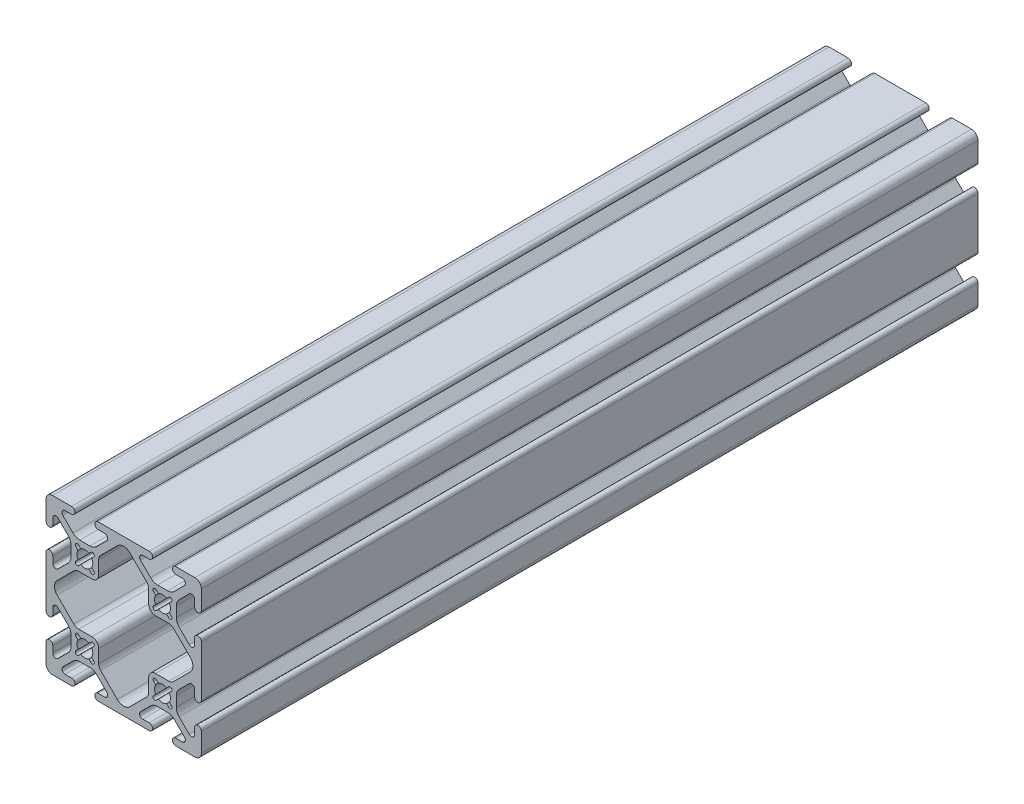
SolidWorks part; units mm, degrees
material "6105-T5 Aluminum"
ref_plane "Front Plane" through (0, 0, 0) normal (0, 0, 1) x (1, 0, 0)
ref_plane "Top Plane" through (0, 0, 0) normal (0, 1, 0) x (1, 0, 0)
ref_plane "Right Plane" through (0, 0, 0) normal (1, 0, 0) x (0, 0, -1)
sketch "Sketch1" plane through (0, 0, 0) normal (0, 0, 1) x (1, 0, 0)
  line L0 (-14.6692, 15.5605) -> (-14.0405, 14.9319)
  line L1 (-11.3595, 14.9319) -> (-10.7308, 15.5605)
  line L2 (-9.8395, 14.6692) -> (-10.4681, 14.0405)
  line L3 (-10.4681, 11.3595) -> (-9.8395, 10.7308)
  line L4 (-10.7308, 9.8395) -> (-11.3595, 10.4681)
  line L5 (-14.0405, 10.4681) -> (-14.6692, 9.8395)
  line L6 (-15.5605, 10.7308) -> (-14.9319, 11.3595)
  line L7 (-14.9319, 14.0405) -> (-15.5605, 14.6692)
  line L8 (11.3595, 10.4681) -> (10.7308, 9.8395)
  line L9 (9.8395, 10.7308) -> (10.4681, 11.3595)
  line L10 (10.4681, 14.0405) -> (9.8395, 14.6692)
  line L11 (10.7308, 15.5605) -> (11.3595, 14.9319)
  line L12 (14.0405, 14.9319) -> (14.6692, 15.5605)
  line L13 (15.5605, 14.6692) -> (14.9319, 14.0405)
  line L14 (14.9319, 11.3595) -> (15.5605, 10.7308)
  line L15 (14.6692, 9.8395) -> (14.0405, 10.4681)
  line L16 (-14.6692, -9.8395) -> (-14.0405, -10.4681)
  line L17 (-11.3595, -10.4681) -> (-10.7308, -9.8395)
  line L18 (-9.8395, -10.7308) -> (-10.4681, -11.3595)
  line L19 (-10.4681, -14.0405) -> (-9.8395, -14.6692)
  line L20 (-10.7308, -15.5605) -> (-11.3595, -14.9319)
  line L21 (-14.0405, -14.9319) -> (-14.6692, -15.5605)
  line L22 (-15.5605, -14.6692) -> (-14.9319, -14.0405)
  line L23 (-14.9319, -11.3595) -> (-15.5605, -10.7308)
  line L24 (10.7308, -9.8395) -> (11.3595, -10.4681)
  line L25 (14.0405, -10.4681) -> (14.6692, -9.8395)
  line L26 (15.5605, -10.7308) -> (14.9319, -11.3595)
  line L27 (14.9319, -14.0405) -> (15.5605, -14.6692)
  line L28 (14.6692, -15.5605) -> (14.0405, -14.9319)
  line L29 (11.3595, -14.9319) -> (10.7308, -15.5605)
  line L30 (9.8395, -14.6692) -> (10.4681, -14.0405)
  line L31 (10.4681, -11.3595) -> (9.8395, -10.7308)
  line L32 (7.5356, -16.3017) -> (2.0587, -21.7787)
  line L33 (-2.0587, -21.7787) -> (-7.5356, -16.3017)
  line L34 (-8.1828, -14.7392) -> (-8.1828, -10.3926)
  line L35 (-10.3926, -8.1828) -> (-14.7392, -8.1828)
  line L36 (-16.3017, -7.5356) -> (-21.7787, -2.0587)
  line L37 (-21.7787, 2.0587) -> (-16.3017, 7.5356)
  line L38 (-14.7392, 8.1828) -> (-10.3926, 8.1828)
  line L39 (-8.1828, 10.3926) -> (-8.1828, 14.7392)
  line L40 (-7.5356, 16.3017) -> (-2.0587, 21.7787)
  line L41 (2.0587, 21.7787) -> (7.5356, 16.3017)
  line L42 (8.1828, 14.7392) -> (8.1828, 10.3926)
  line L43 (10.3926, 8.1828) -> (14.7392, 8.1828)
  line L44 (16.3017, 7.5356) -> (21.7787, 2.0587)
  line L45 (21.7787, -2.0587) -> (16.3017, -7.5356)
  line L46 (14.7392, -8.1828) -> (10.3926, -8.1828)
  line L47 (8.1828, -10.3926) -> (8.1828, -14.7392)
  line L48 (25.4, 17.0561) -> (25.4, 23.2918)
  line L49 (23.2918, 25.4) -> (17.0561, 25.4)
  line L50 (17.0561, 23.1902) -> (19.1749, 23.1902)
  line L51 (19.8933, 21.4558) -> (16.5846, 18.1471)
  line L52 (14.3396, 17.2172) -> (11.0604, 17.2172)
  line L53 (8.8154, 18.1471) -> (5.5067, 21.4558)
  line L54 (6.2251, 23.1902) -> (8.3439, 23.1902)
  line L55 (8.3439, 25.4) -> (-8.3439, 25.4)
  line L56 (-8.3439, 23.1902) -> (-6.2251, 23.1902)
  line L57 (-5.5067, 21.4558) -> (-8.8154, 18.1471)
  line L58 (-11.0604, 17.2172) -> (-14.3396, 17.2172)
  line L59 (-16.5846, 18.1471) -> (-19.8933, 21.4558)
  line L60 (-19.1749, 23.1902) -> (-17.0561, 23.1902)
  line L61 (-17.0561, 25.4) -> (-23.2918, 25.4)
  line L62 (-25.4, 23.2918) -> (-25.4, 17.0561)
  line L63 (-23.1902, 17.0561) -> (-23.1902, 19.1749)
  line L64 (-21.4558, 19.8933) -> (-18.1471, 16.5846)
  line L65 (-17.2172, 14.3396) -> (-17.2172, 11.0604)
  line L66 (-18.1471, 8.8154) -> (-21.4558, 5.5067)
  line L67 (-23.1902, 6.2251) -> (-23.1902, 8.3439)
  line L68 (-25.4, 8.3439) -> (-25.4, -8.3439)
  line L69 (-23.1902, -8.3439) -> (-23.1902, -6.2251)
  line L70 (-21.4558, -5.5067) -> (-18.1471, -8.8154)
  line L71 (-17.2172, -11.0604) -> (-17.2172, -14.3396)
  line L72 (-18.1471, -16.5846) -> (-21.4558, -19.8933)
  line L73 (-23.1902, -19.1749) -> (-23.1902, -17.0561)
  line L74 (-25.4, -17.0561) -> (-25.4, -23.2918)
  line L75 (-23.2918, -25.4) -> (-17.0561, -25.4)
  line L76 (-17.0561, -23.1902) -> (-19.1749, -23.1902)
  line L77 (-19.8933, -21.4558) -> (-16.5846, -18.1471)
  line L78 (-14.3396, -17.2172) -> (-11.0604, -17.2172)
  line L79 (-8.8154, -18.1471) -> (-5.5067, -21.4558)
  line L80 (-6.2251, -23.1902) -> (-8.3439, -23.1902)
  line L81 (-8.3439, -25.4) -> (8.3439, -25.4)
  line L82 (8.3439, -23.1902) -> (6.2251, -23.1902)
  line L83 (5.5067, -21.4558) -> (8.8154, -18.1471)
  line L84 (11.0604, -17.2172) -> (14.3396, -17.2172)
  line L85 (16.5846, -18.1471) -> (19.8933, -21.4558)
  line L86 (19.1749, -23.1902) -> (17.0561, -23.1902)
  line L87 (17.0561, -25.4) -> (23.2918, -25.4)
  line L88 (25.4, -23.2918) -> (25.4, -17.0561)
  line L89 (23.1902, -17.0561) -> (23.1902, -19.1749)
  line L90 (21.4558, -19.8933) -> (18.1471, -16.5846)
  line L91 (17.2172, -14.3396) -> (17.2172, -11.0604)
  line L92 (18.1471, -8.8154) -> (21.4558, -5.5067)
  line L93 (23.1902, -6.2251) -> (23.1902, -8.3439)
  line L94 (25.4, -8.3439) -> (25.4, 8.3439)
  line L95 (23.1902, 8.3439) -> (23.1902, 6.2251)
  line L96 (21.4558, 5.5067) -> (18.1471, 8.8154)
  line L97 (17.2172, 11.0604) -> (17.2172, 14.3396)
  line L98 (18.1471, 16.5846) -> (21.4558, 19.8933)
  line L99 (23.1902, 19.1749) -> (23.1902, 17.0561)
  arc A0 (-11.3595, 14.9319) -> (-14.0405, 14.9319) centre (-12.7, 12.7) ccw
  arc A1 (-9.8395, 14.6692) -> (-10.7308, 15.5605) centre (-10.2304, 15.1696) ccw
  arc A2 (-10.4681, 11.3595) -> (-10.4681, 14.0405) centre (-12.7, 12.7) ccw
  arc A3 (-10.7308, 9.8395) -> (-9.8395, 10.7308) centre (-10.2304, 10.2304) ccw
  arc A4 (-14.0405, 10.4681) -> (-11.3595, 10.4681) centre (-12.7, 12.7) ccw
  arc A5 (-15.5605, 10.7308) -> (-14.6692, 9.8395) centre (-15.1696, 10.2304) ccw
  arc A6 (-14.9319, 14.0405) -> (-14.9319, 11.3595) centre (-12.7, 12.7) ccw
  arc A7 (-14.6692, 15.5605) -> (-15.5605, 14.6692) centre (-15.1696, 15.1696) ccw
  arc A8 (9.8395, 10.7308) -> (10.7308, 9.8395) centre (10.2304, 10.2304) ccw
  arc A9 (10.4681, 14.0405) -> (10.4681, 11.3595) centre (12.7, 12.7) ccw
  arc A10 (10.7308, 15.5605) -> (9.8395, 14.6692) centre (10.2304, 15.1696) ccw
  arc A11 (14.0405, 14.9319) -> (11.3595, 14.9319) centre (12.7, 12.7) ccw
  arc A12 (15.5605, 14.6692) -> (14.6692, 15.5605) centre (15.1696, 15.1696) ccw
  arc A13 (14.9319, 11.3595) -> (14.9319, 14.0405) centre (12.7, 12.7) ccw
  arc A14 (14.6692, 9.8395) -> (15.5605, 10.7308) centre (15.1696, 10.2304) ccw
  arc A15 (11.3595, 10.4681) -> (14.0405, 10.4681) centre (12.7, 12.7) ccw
  arc A16 (-11.3595, -10.4681) -> (-14.0405, -10.4681) centre (-12.7, -12.7) ccw
  arc A17 (-9.8395, -10.7308) -> (-10.7308, -9.8395) centre (-10.2304, -10.2304) ccw
  arc A18 (-10.4681, -14.0405) -> (-10.4681, -11.3595) centre (-12.7, -12.7) ccw
  arc A19 (-10.7308, -15.5605) -> (-9.8395, -14.6692) centre (-10.2304, -15.1696) ccw
  arc A20 (-14.0405, -14.9319) -> (-11.3595, -14.9319) centre (-12.7, -12.7) ccw
  arc A21 (-15.5605, -14.6692) -> (-14.6692, -15.5605) centre (-15.1696, -15.1696) ccw
  arc A22 (-14.9319, -11.3595) -> (-14.9319, -14.0405) centre (-12.7, -12.7) ccw
  arc A23 (-14.6692, -9.8395) -> (-15.5605, -10.7308) centre (-15.1696, -10.2304) ccw
  arc A24 (14.0405, -10.4681) -> (11.3595, -10.4681) centre (12.7, -12.7) ccw
  arc A25 (15.5605, -10.7308) -> (14.6692, -9.8395) centre (15.1696, -10.2304) ccw
  arc A26 (14.9319, -14.0405) -> (14.9319, -11.3595) centre (12.7, -12.7) ccw
  arc A27 (14.6692, -15.5605) -> (15.5605, -14.6692) centre (15.1696, -15.1696) ccw
  arc A28 (11.3595, -14.9319) -> (14.0405, -14.9319) centre (12.7, -12.7) ccw
  arc A29 (9.8395, -14.6692) -> (10.7308, -15.5605) centre (10.2304, -15.1696) ccw
  arc A30 (10.4681, -11.3595) -> (10.4681, -14.0405) centre (12.7, -12.7) ccw
  arc A31 (10.7308, -9.8395) -> (9.8395, -10.7308) centre (10.2304, -10.2304) ccw
  arc A32 (-2.0587, -21.7787) -> (2.0587, -21.7787) centre (0, -19.72) ccw
  arc A33 (-8.1828, -14.7392) -> (-7.5356, -16.3017) centre (-5.973, -14.7392) ccw
  arc A34 (-8.1828, -10.3926) -> (-10.3926, -8.1828) centre (-10.3926, -10.3926) ccw
  arc A35 (-16.3017, -7.5356) -> (-14.7392, -8.1828) centre (-14.7392, -5.973) ccw
  arc A36 (-21.7787, 2.0587) -> (-21.7787, -2.0587) centre (-19.72, 0) ccw
  arc A37 (-14.7392, 8.1828) -> (-16.3017, 7.5356) centre (-14.7392, 5.973) ccw
  arc A38 (-10.3926, 8.1828) -> (-8.1828, 10.3926) centre (-10.3926, 10.3926) ccw
  arc A39 (-7.5356, 16.3017) -> (-8.1828, 14.7392) centre (-5.973, 14.7392) ccw
  arc A40 (2.0587, 21.7787) -> (-2.0587, 21.7787) centre (0, 19.72) ccw
  arc A41 (8.1828, 14.7392) -> (7.5356, 16.3017) centre (5.973, 14.7392) ccw
  arc A42 (8.1828, 10.3926) -> (10.3926, 8.1828) centre (10.3926, 10.3926) ccw
  arc A43 (16.3017, 7.5356) -> (14.7392, 8.1828) centre (14.7392, 5.973) ccw
  arc A44 (21.7787, -2.0587) -> (21.7787, 2.0587) centre (19.72, 0) ccw
  arc A45 (14.7392, -8.1828) -> (16.3017, -7.5356) centre (14.7392, -5.973) ccw
  arc A46 (10.3926, -8.1828) -> (8.1828, -10.3926) centre (10.3926, -10.3926) ccw
  arc A47 (7.5356, -16.3017) -> (8.1828, -14.7392) centre (5.973, -14.7392) ccw
  arc A48 (23.1902, 17.0561) -> (25.4, 17.0561) centre (24.2951, 17.0561) ccw
  arc A49 (25.4, 23.2918) -> (23.2918, 25.4) centre (23.2918, 23.2918) ccw
  arc A50 (17.0561, 25.4) -> (17.0561, 23.1902) centre (17.0561, 24.2951) ccw
  arc A51 (19.8933, 21.4558) -> (19.1749, 23.1902) centre (19.1749, 22.1742) ccw
  arc A52 (14.3396, 17.2172) -> (16.5846, 18.1471) centre (14.3396, 20.3922) ccw
  arc A53 (8.8154, 18.1471) -> (11.0604, 17.2172) centre (11.0604, 20.3922) ccw
  arc A54 (6.2251, 23.1902) -> (5.5067, 21.4558) centre (6.2251, 22.1742) ccw
  arc A55 (8.3439, 23.1902) -> (8.3439, 25.4) centre (8.3439, 24.2951) ccw
  arc A56 (-8.3439, 25.4) -> (-8.3439, 23.1902) centre (-8.3439, 24.2951) ccw
  arc A57 (-5.5067, 21.4558) -> (-6.2251, 23.1902) centre (-6.2251, 22.1742) ccw
  arc A58 (-11.0604, 17.2172) -> (-8.8154, 18.1471) centre (-11.0604, 20.3922) ccw
  arc A59 (-16.5846, 18.1471) -> (-14.3396, 17.2172) centre (-14.3396, 20.3922) ccw
  arc A60 (-19.1749, 23.1902) -> (-19.8933, 21.4558) centre (-19.1749, 22.1742) ccw
  arc A61 (-17.0561, 23.1902) -> (-17.0561, 25.4) centre (-17.0561, 24.2951) ccw
  arc A62 (-23.2918, 25.4) -> (-25.4, 23.2918) centre (-23.2918, 23.2918) ccw
  arc A63 (-25.4, 17.0561) -> (-23.1902, 17.0561) centre (-24.2951, 17.0561) ccw
  arc A64 (-21.4558, 19.8933) -> (-23.1902, 19.1749) centre (-22.1742, 19.1749) ccw
  arc A65 (-17.2172, 14.3396) -> (-18.1471, 16.5846) centre (-20.3922, 14.3396) ccw
  arc A66 (-18.1471, 8.8154) -> (-17.2172, 11.0604) centre (-20.3922, 11.0604) ccw
  arc A67 (-23.1902, 6.2251) -> (-21.4558, 5.5067) centre (-22.1742, 6.2251) ccw
  arc A68 (-23.1902, 8.3439) -> (-25.4, 8.3439) centre (-24.2951, 8.3439) ccw
  arc A69 (-25.4, -8.3439) -> (-23.1902, -8.3439) centre (-24.2951, -8.3439) ccw
  arc A70 (-21.4558, -5.5067) -> (-23.1902, -6.2251) centre (-22.1742, -6.2251) ccw
  arc A71 (-17.2172, -11.0604) -> (-18.1471, -8.8154) centre (-20.3922, -11.0604) ccw
  arc A72 (-18.1471, -16.5846) -> (-17.2172, -14.3396) centre (-20.3922, -14.3396) ccw
  arc A73 (-23.1902, -19.1749) -> (-21.4558, -19.8933) centre (-22.1742, -19.1749) ccw
  arc A74 (-23.1902, -17.0561) -> (-25.4, -17.0561) centre (-24.2951, -17.0561) ccw
  arc A75 (-25.4, -23.2918) -> (-23.2918, -25.4) centre (-23.2918, -23.2918) ccw
  arc A76 (-17.0561, -25.4) -> (-17.0561, -23.1902) centre (-17.0561, -24.2951) ccw
  arc A77 (-19.8933, -21.4558) -> (-19.1749, -23.1902) centre (-19.1749, -22.1742) ccw
  arc A78 (-14.3396, -17.2172) -> (-16.5846, -18.1471) centre (-14.3396, -20.3922) ccw
  arc A79 (-8.8154, -18.1471) -> (-11.0604, -17.2172) centre (-11.0604, -20.3922) ccw
  arc A80 (-6.2251, -23.1902) -> (-5.5067, -21.4558) centre (-6.2251, -22.1742) ccw
  arc A81 (-8.3439, -23.1902) -> (-8.3439, -25.4) centre (-8.3439, -24.2951) ccw
  arc A82 (8.3439, -25.4) -> (8.3439, -23.1902) centre (8.3439, -24.2951) ccw
  arc A83 (5.5067, -21.4558) -> (6.2251, -23.1902) centre (6.2251, -22.1742) ccw
  arc A84 (11.0604, -17.2172) -> (8.8154, -18.1471) centre (11.0604, -20.3922) ccw
  arc A85 (16.5846, -18.1471) -> (14.3396, -17.2172) centre (14.3396, -20.3922) ccw
  arc A86 (19.1749, -23.1902) -> (19.8933, -21.4558) centre (19.1749, -22.1742) ccw
  arc A87 (17.0561, -23.1902) -> (17.0561, -25.4) centre (17.0561, -24.2951) ccw
  arc A88 (23.2918, -25.4) -> (25.4, -23.2918) centre (23.2918, -23.2918) ccw
  arc A89 (25.4, -17.0561) -> (23.1902, -17.0561) centre (24.2951, -17.0561) ccw
  arc A90 (21.4558, -19.8933) -> (23.1902, -19.1749) centre (22.1742, -19.1749) ccw
  arc A91 (17.2172, -14.3396) -> (18.1471, -16.5846) centre (20.3922, -14.3396) ccw
  arc A92 (18.1471, -8.8154) -> (17.2172, -11.0604) centre (20.3922, -11.0604) ccw
  arc A93 (23.1902, -6.2251) -> (21.4558, -5.5067) centre (22.1742, -6.2251) ccw
  arc A94 (23.1902, -8.3439) -> (25.4, -8.3439) centre (24.2951, -8.3439) ccw
  arc A95 (25.4, 8.3439) -> (23.1902, 8.3439) centre (24.2951, 8.3439) ccw
  arc A96 (21.4558, 5.5067) -> (23.1902, 6.2251) centre (22.1742, 6.2251) ccw
  arc A97 (17.2172, 11.0604) -> (18.1471, 8.8154) centre (20.3922, 11.0604) ccw
  arc A98 (18.1471, 16.5846) -> (17.2172, 14.3396) centre (20.3922, 14.3396) ccw
  arc A99 (23.1902, 19.1749) -> (21.4558, 19.8933) centre (22.1742, 19.1749) ccw
extrude "Extrude1" add sketch "Sketch1" against normal blind 254
